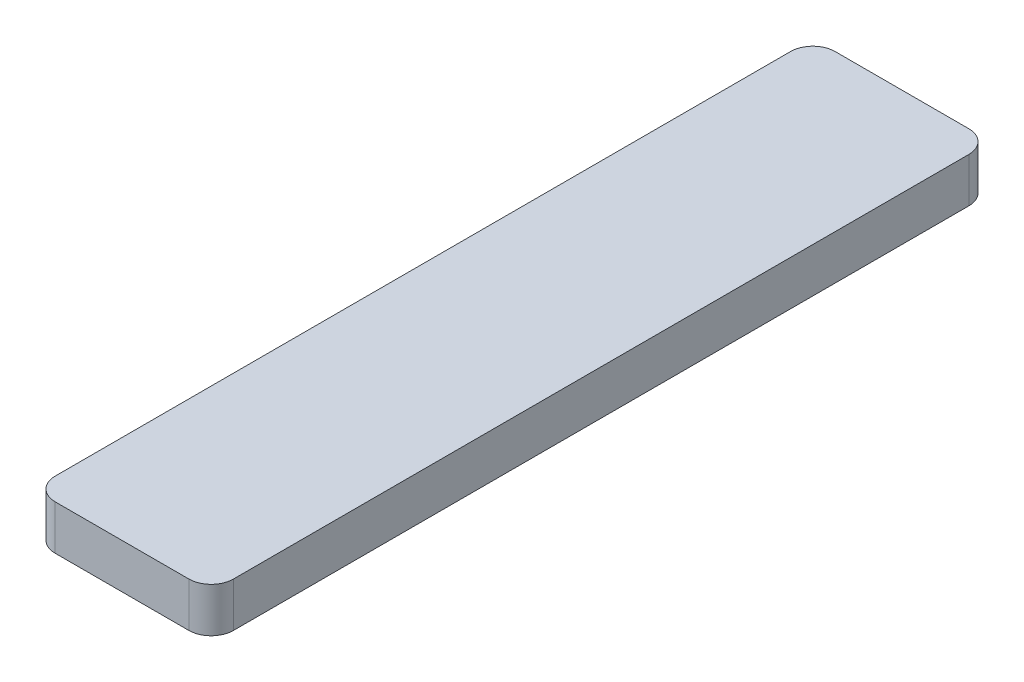
SolidWorks part; units mm, degrees
ref_plane "前视基准面" through (0, 0, 0) normal (0, 0, 1) x (1, 0, 0)
ref_plane "上视基准面" through (0, 0, 0) normal (0, 1, 0) x (1, 0, 0)
ref_plane "右视基准面" through (0, 0, 0) normal (1, 0, 0) x (0, 0, -1)
other "Configuration Table"
sketch "草图1" plane through (0, 0, 0) normal (0, 1, 0) x (1, 0, 0)
  line L1 (8, -35) -> (-8, -35)
  line L2 (8, -35) -> (8, 35)
  line L3 (8, 35) -> (-8, 35)
  line L4 (-8, -35) -> (-8, 35)
  line L5 (8, -35) -> (-8, 35) construction
  line L6 (8, 35) -> (-8, -35) construction
  point P0 (0, 0)
  dimension "D1" = 16
  dimension "D2" = 70
extrude "凸台-拉伸1" add sketch "草图1" along normal blind 4
fillet "圆角1" radius 2 4 edges at (-8, 2, 35) (8, 2, 35) (8, 2, -35) (-8, 2, -35)
